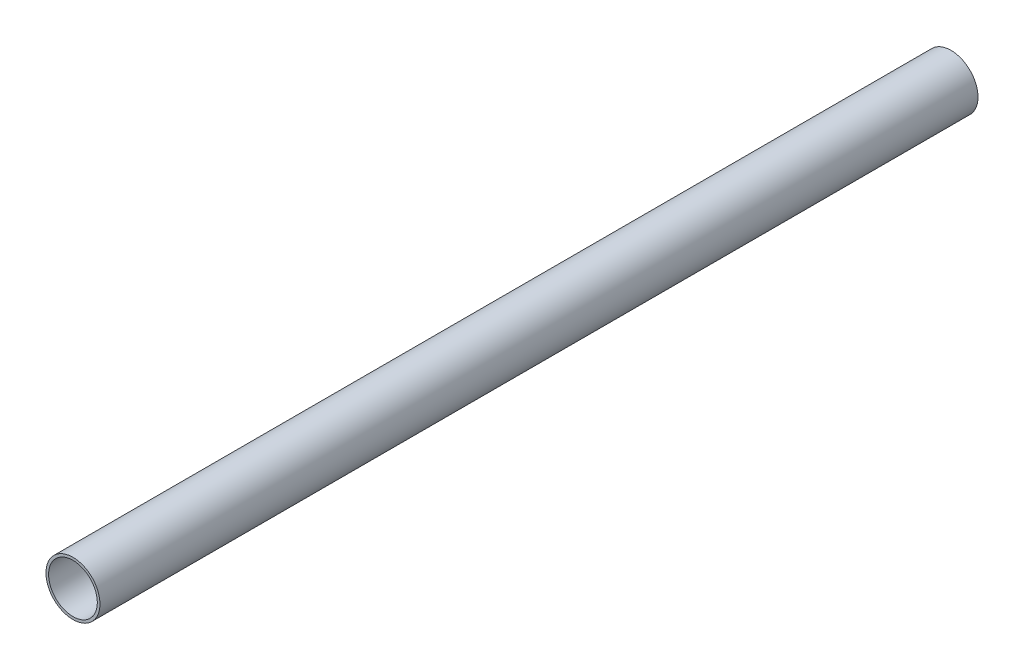
SolidWorks part; units mm, degrees
ref_plane "Front Plane" through (0, 0, 0) normal (0, 0, 1) x (1, 0, 0)
ref_plane "Top Plane" through (0, 0, 0) normal (0, 1, 0) x (1, 0, 0)
ref_plane "Right Plane" through (0, 0, 0) normal (1, 0, 0) x (0, 0, -1)
sketch "Sketch1" plane through (0, 0, 0) normal (0, 0, 1) x (1, 0, 0)
  circle A0 centre (0, 0) radius 0.375
  circle A1 centre (0, 0) radius 0.415
  dimension "D1" = 0.83
  dimension "D2" = 0.75
extrude "Boss-Extrude1" add sketch "Sketch1" along normal blind 13.5
